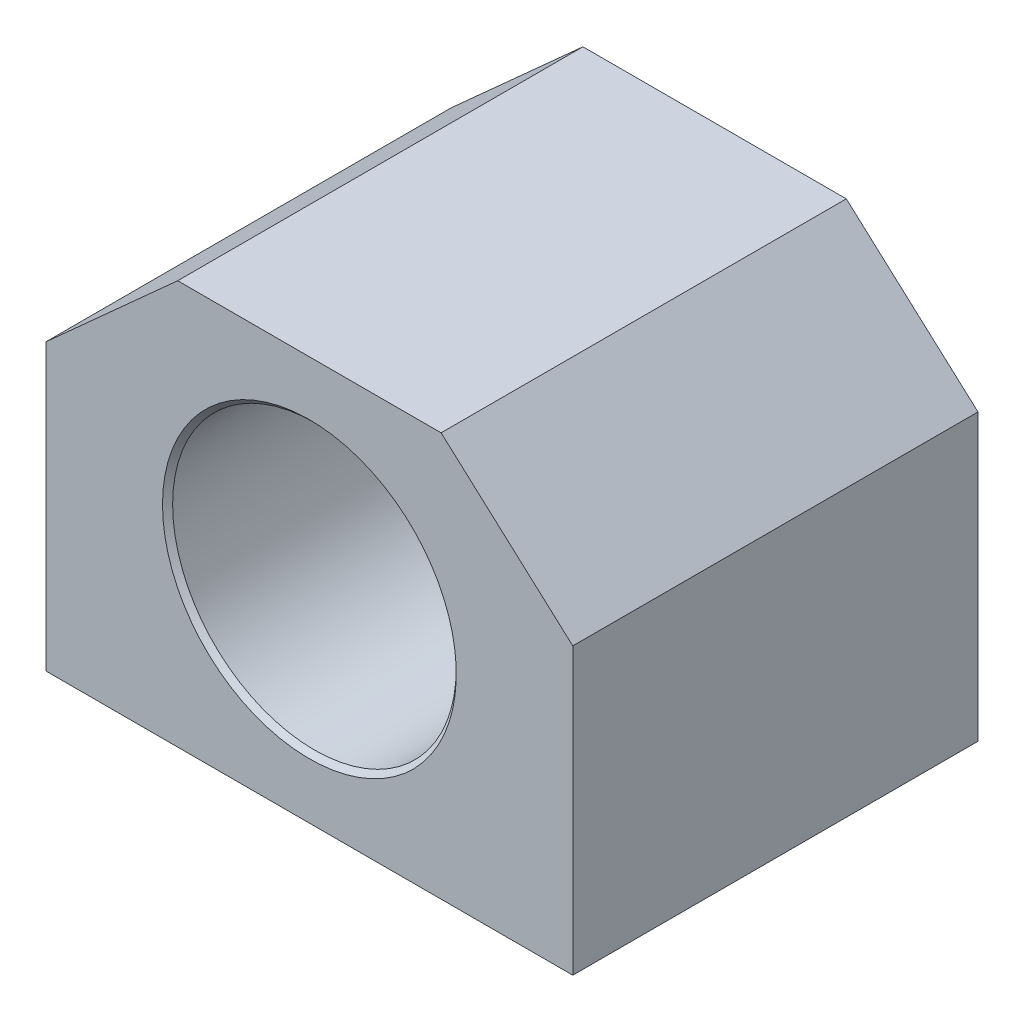
SolidWorks part; units mm, degrees
material "6061-T6 (SS)"
ref_plane "Alzado" through (0, 0, 0) normal (0, 0, 1) x (1, 0, 0)
ref_plane "Planta" through (0, 0, 0) normal (0, 1, 0) x (1, 0, 0)
ref_plane "Vista lateral" through (0, 0, 0) normal (1, 0, 0) x (0, 0, -1)
sketch "Croquis1" plane through (0, 0, 0) normal (0, 0, 1) x (1, 0, 0)
  line L0 (26, 0) -> (-26, 0)
  line L1 (-26, 0) -> (-26, 28.1546)
  line L2 (-26, 28.1546) -> (-13, 39.87)
  line L3 (-13, 39.87) -> (13, 39.87)
  line L4 (13, 39.87) -> (26, 28.1546)
  line L5 (26, 28.1546) -> (26, 0)
  line L6 (0, 0) -> (0, 53.3352) construction
  point P4 (0, 0)
  dimension "D1" = 52
  dimension "D2" = 39.87
  dimension "D3" = 13
  dimension "D4" = 13
  dimension "D5" = 17.5
extrude "Saliente-Extruir1" add sketch "Croquis1" along normal mid plane 40
sketch "Croquis2" plane through (0, 0, 20) normal (0, 0, 1) x (1, 0, 0)
  line L1 (-26, 0) -> (26, 0) construction
  circle A0 centre (0, 20) radius 14
  dimension "D1" = 28
  dimension "D2" = 20
extrude "Cortar-Extruir1" cut sketch "Croquis2" against normal through all
chamfer "Chaflán1" distance 0.5 angle 45 2 edges at (14, 20, -20) (14, 20, 20)
sketch "Croquis3" plane through (0, 0, 0) normal (0, -1, 0) x (1, 0, 0)
  line L0 (0, 0) -> (0, 29.6374) construction
  line L1 (0, 0) -> (32.543, 0) construction
  point P3 (-20, 12)
  point P4 (20, 12)
  point P5 (20, -12)
  point P6 (-20, -12)
  dimension "D1" = 40
  dimension "D2" = 24
hole_wizard "Taladro roscado M5x0.81" positions "Croquis4" profile "Croquis5" tap size "M5x0.8" standard "Ansi Metric"
sketch "Croquis4" plane through (0, 0, 0) normal (0, -1, 0) x (-1, 0, 0)
  point P0 (-20, -12)
  point P3 (20, -12)
  point P6 (20, 12)
  point P9 (-20, 12)
sketch "Croquis5" plane through (20, 0, 12) normal (1, 0, 0) x (0, 0, -1)
  line L0 (0, 0) -> (0, 17.2618)
  line L1 (0, 17.2618) -> (2.1, 16)
  line L2 (2.1, 16) -> (2.1, 0)
  line L5 (2.1, 0) -> (0, 0)
  line L10 (0, 17.2618) -> (-2.1, 16) construction
  line L11 (0, -6.35) -> (0, 107.95) construction
  dimension "Diámetro de perforador para roscar" = 4.2
  dimension "Profundidad de perforador para roscar" = 16
  dimension "Ángulo de perforador" = 118
cosmetic thread "Rosca de taladro1" parameters "D1"=14, "D2"=5
cosmetic thread "Rosca de taladro2" parameters "D1"=14, "D2"=5
cosmetic thread "Rosca de taladro3" parameters "D1"=14, "D2"=5
cosmetic thread "Rosca de taladro4" parameters "D1"=14, "D2"=5
